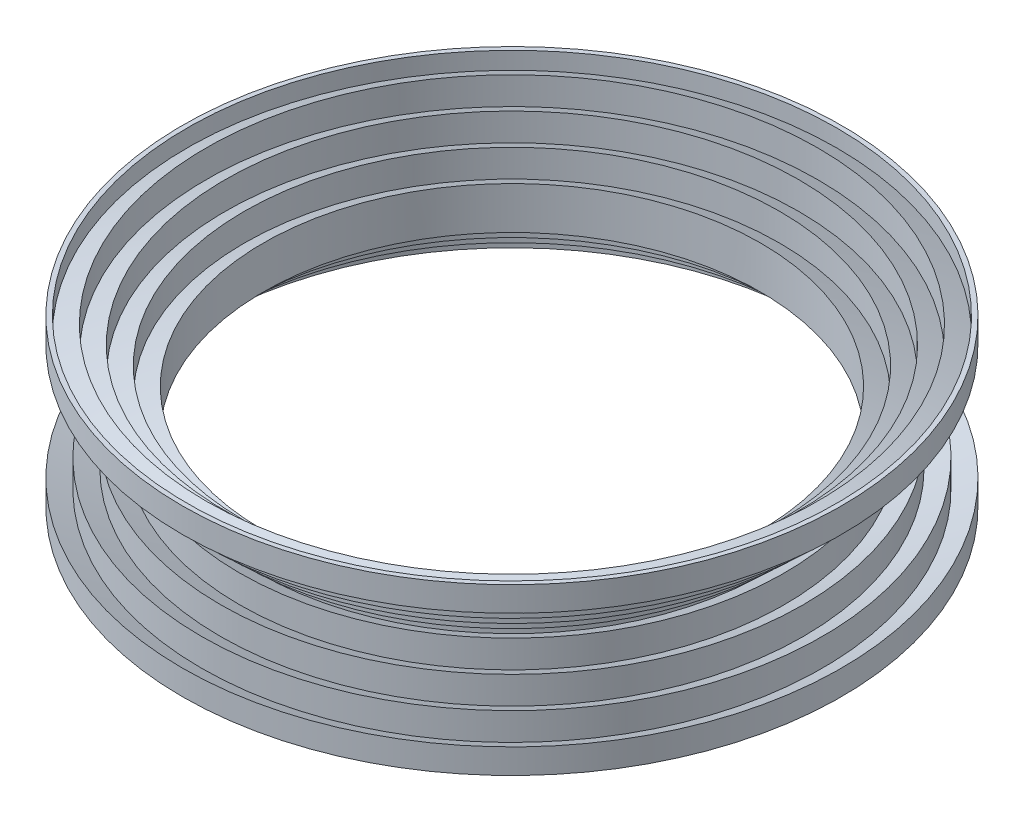
SolidWorks part; units mm, degrees
ref_plane "정면" through (0, 0, 0) normal (0, 0, 1) x (1, 0, 0)
ref_plane "윗면" through (0, 0, 0) normal (0, 1, 0) x (1, 0, 0)
ref_plane "우측면" through (0, 0, 0) normal (1, 0, 0) x (0, 0, -1)
sketch "스케치1" plane through (0, 0, 0) normal (0, 1, 0) x (1, 0, 0)
  circle A7 centre (0, 0) radius 35.8938
  dimension "D2" = 71.7876
extrude "보스-돌출1" add sketch "스케치1" along normal blind 1.2
ref_plane "평면1" through (0, 9, 0) normal (0, -1, 0) x (-1, 0, 0)
sketch "스케치3" plane through (0, 9, 0) normal (0, -1, 0) x (-1, 0, 0)
  circle A0 centre (0, 0) radius 27.5887
  dimension "D1" = 55.1775
sketch "스케치4" plane through (0, 0, 0) normal (1, 0, 0) x (0, 0, -1)
  line L1 (-27.5887, 9) -> (27.5887, 9) construction
  line L2 (0, 9) -> (0, 1.2) construction
  line L3 (35.8938, 1.2) -> (-35.8938, 1.2) construction
  line L4 (-35.8938, 1.2) -> (-35.8938, 2.7)
  line L5 (-35.8938, 1.2) -> (-35.8938, -0.3)
  line L6 (-35.8938, 1.2) -> (-35.8938, 0) construction
  line L7 (-35.8938, 1.2) -> (-27.5887, 9) construction
  line L8 (0, 9) -> (-27.5887, 9) construction
  line L9 (-33.8164, 3.1511) -> (-33.8164, 4.6511)
  line L10 (-33.8164, 3.1511) -> (-33.8164, 1.6511)
  line L11 (-31.7389, 5.1022) -> (-31.7389, 6.6022)
  line L12 (-31.7389, 5.1022) -> (-31.7389, 3.6022)
  line L13 (0, 9) -> (27.5887, 9) construction
  line L14 (-27.5887, 9) -> (0, 9)
  line L15 (0, 9) -> (0, 1.2)
  line L16 (-35.8938, 1.2) -> (0, 1.2)
  line L17 (-29.6615, 7.0533) -> (-29.6615, 8.5533)
  line L18 (-29.6615, 7.0533) -> (-29.6615, 5.5533)
  line L19 (-27.5841, 9.0044) -> (-27.5841, 10.5044)
  line L20 (-27.5841, 9.0044) -> (-27.5841, 7.5044)
  line L21 (-35.8938, 2.7) -> (-33.8164, 1.6511)
  line L22 (-33.8164, 4.6511) -> (-31.7389, 3.6022)
  line L23 (-31.7389, 6.6022) -> (-29.6615, 5.5533)
  line L24 (-29.6615, 8.5533) -> (-27.5841, 7.5044)
  dimension "D1" = 1.5
revolve "회전1" add sketch "스케치4" angle 360 about L15
mirror "대칭 복사1" about plane through (0, 9, 0) normal (0, -1, 0) of "보스-돌출1", "회전1"
shell "쉘1" thickness 0.5
